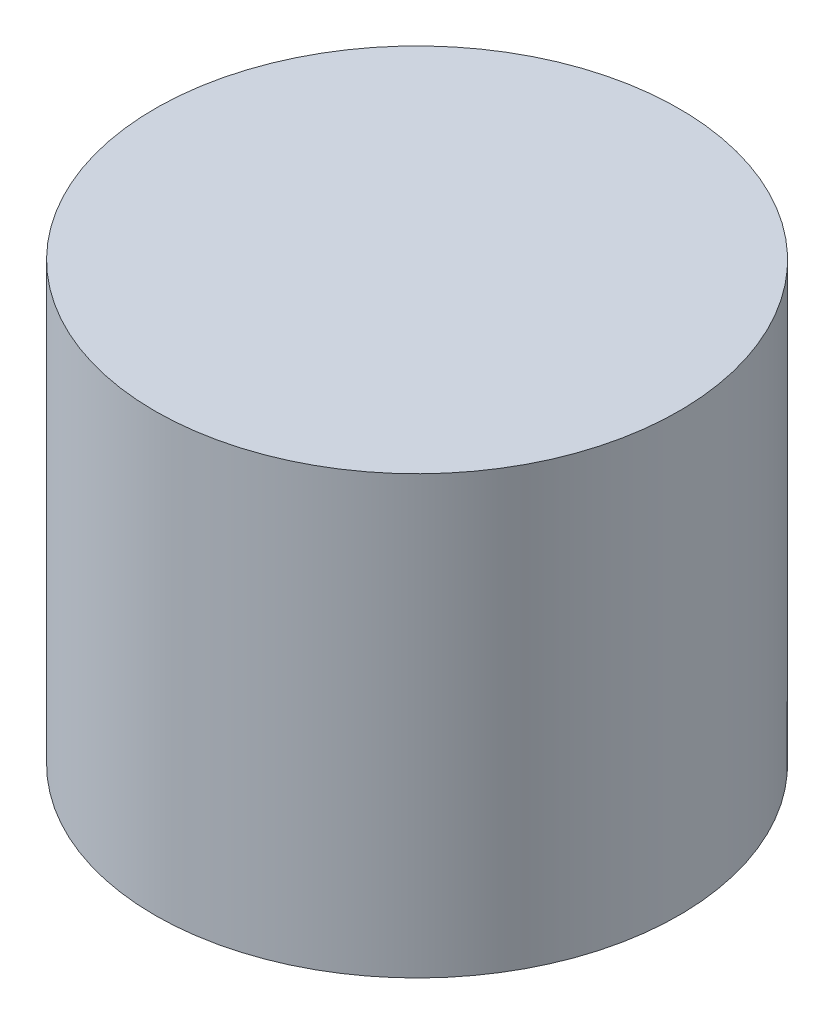
SolidWorks part; units mm, degrees
ref_plane "Front Plane" through (0, 0, 0) normal (0, 0, 1) x (1, 0, 0)
ref_plane "Top Plane" through (0, 0, 0) normal (0, 1, 0) x (1, 0, 0)
ref_plane "Right Plane" through (0, 0, 0) normal (1, 0, 0) x (0, 0, -1)
sketch "Sketch1" plane through (0, 0, 0) normal (0, 1, 0) x (1, 0, 0)
  circle A0 centre (0, 0) radius 90
  dimension "D1" = 180
extrude "Boss-Extrude1" add sketch "Sketch1" along normal blind 150
